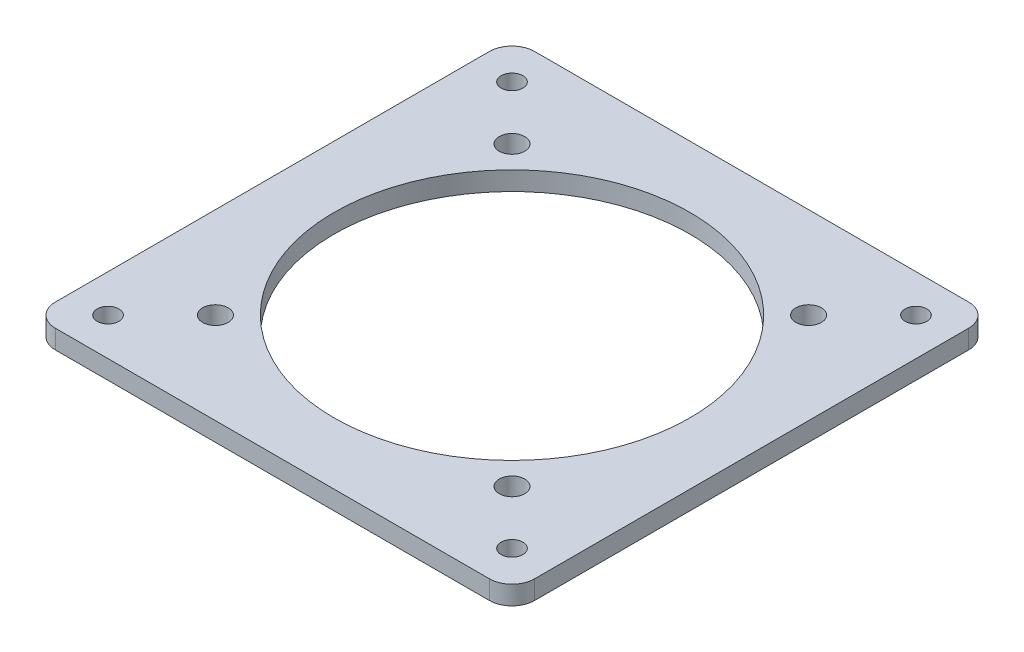
SolidWorks part; units mm, degrees
material "Maple"
ref_plane "Front Plane" through (0, 0, 0) normal (0, 0, 1) x (1, 0, 0)
ref_plane "Top Plane" through (0, 0, 0) normal (0, 1, 0) x (1, 0, 0)
ref_plane "Right Plane" through (0, 0, 0) normal (1, 0, 0) x (0, 0, -1)
sketch "Sketch1" plane through (0, 0, 0) normal (0, 1, 0) x (1, 0, 0)
  line L7 (-36.59, 40.4) -> (36.59, 40.4)
  line L8 (-40.4, 36.59) -> (-40.4, -36.59)
  line L9 (-36.59, -40.4) -> (36.59, -40.4)
  line L10 (40.4, 36.59) -> (40.4, -36.59)
  line L11 (-40.4, 40.4) -> (40.4, -40.4) construction
  line L12 (-40.4, -40.4) -> (40.4, 40.4) construction
  circle A0 centre (0, 0) radius 30
  circle A1 centre (-25, 25) radius 2.15
  circle A2 centre (25, 25) radius 2.15
  circle A3 centre (25, -25) radius 2.15
  circle A4 centre (-25, -25) radius 2.15
  circle A5 centre (-34.05, 34.05) radius 1.8288
  circle A6 centre (34.05, 34.05) radius 1.8288
  circle A7 centre (34.05, -34.05) radius 1.8288
  circle A8 centre (-34.05, -34.05) radius 1.8288
  arc A9 (36.59, -40.4) -> (40.4, -36.59) centre (36.59, -36.59) ccw
  arc A10 (-36.59, -40.4) -> (-40.4, -36.59) centre (-36.59, -36.59) cw
  arc A11 (-40.4, 36.59) -> (-36.59, 40.4) centre (-36.59, 36.59) cw
  arc A12 (40.4, 36.59) -> (36.59, 40.4) centre (36.59, 36.59) ccw
  point P0 (0, 0)
  point P6 (0, 0)
  dimension "D1" = 60
  dimension "D4" = 4.3
  dimension "D5" = 3.6576
  dimension "D7" = 3.81
  dimension "D2" = 50
  dimension "D3" = 80.8
  dimension "D6" = 6.35
extrude "Boss-Extrude1" add sketch "Sketch1" along normal blind 3.175
